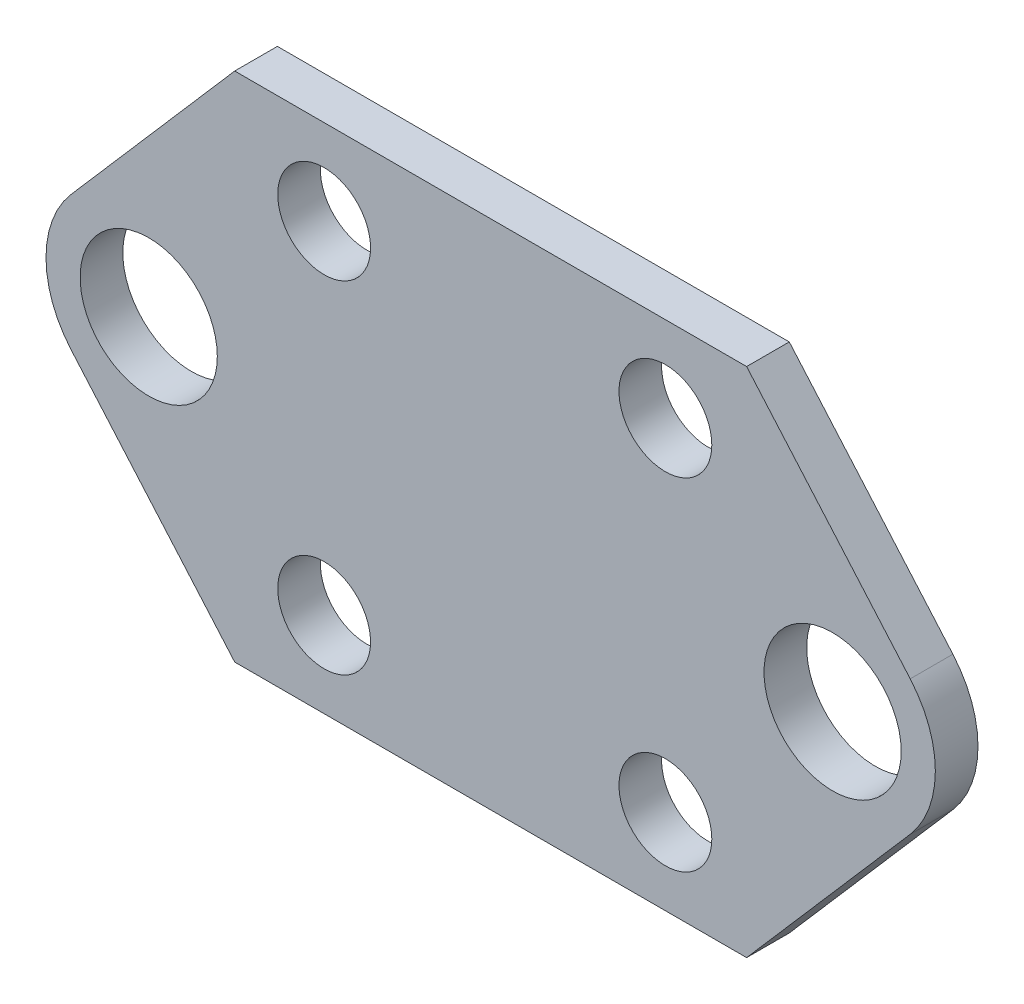
SolidWorks part; units mm, degrees
ref_plane "Alzado" through (0, 0, 0) normal (0, 0, 1) x (1, 0, 0)
ref_plane "Planta" through (0, 0, 0) normal (0, 1, 0) x (1, 0, 0)
ref_plane "Vista lateral" through (0, 0, 0) normal (1, 0, 0) x (0, 0, -1)
sketch "Croquis1" plane through (0, 0, 0) normal (0, 0, 1) x (1, 0, 0)
  line L0 (0, 0) -> (-9.525, 0) construction
  line L1 (-9.525, -9.525) -> (9.525, -9.525)
  line L2 (-9.525, -9.525) -> (-9.525, 9.525)
  line L3 (-9.525, 9.525) -> (9.525, 9.525)
  line L4 (9.525, -9.525) -> (9.525, 9.525)
  line L5 (-9.525, -9.525) -> (9.525, 9.525) construction
  line L6 (-9.525, 9.525) -> (9.525, -9.525) construction
  line L7 (0, 0) -> (0, 9.525) construction
  line L8 (-15.6134, 2.5045) -> (-9.525, 9.525)
  line L9 (-15.6134, -2.5045) -> (-9.525, -9.525)
  line L10 (15.6134, -2.5045) -> (9.525, -9.525)
  line L11 (15.6134, 2.5045) -> (9.525, 9.525)
  circle A0 centre (-6.1976, 6.35) radius 1.7272
  circle A2 centre (6.5024, 6.35) radius 1.7272
  circle A3 centre (-6.1976, -6.35) radius 1.7272
  circle A4 centre (6.5024, -6.35) radius 1.7272
  circle A5 centre (-12.7254, 0) radius 2.5527
  circle A6 centre (-12.7254, 0) radius 3.8227
  circle A7 centre (12.7254, 0) radius 2.5527
  circle A8 centre (12.7254, 0) radius 3.8227
  point P0 (0, 0)
  dimension "D2" = 12.7
  dimension "D3" = 3.175
  dimension "D4" = 3.4544
  dimension "D5" = 3.0226
  dimension "D6" = 3.3274
  dimension "D7" = 5.1054
  dimension "D8" = 20.3454
  dimension "D9" = 1.27
  dimension "D1" = 19.05
extrude "Saliente-Extruir1" add sketch "Croquis1" along normal mid plane 1.5875 contours L2 A6 A5 | A6 L2 L8 | A6 L9 L2 | L2 A6 | L4 A8 L3 L2 A6 L1 A3 A2 A0 A4 | L4 A8 L11 | A8 L4 A7 | A8 L4 | L10 A8 L4
